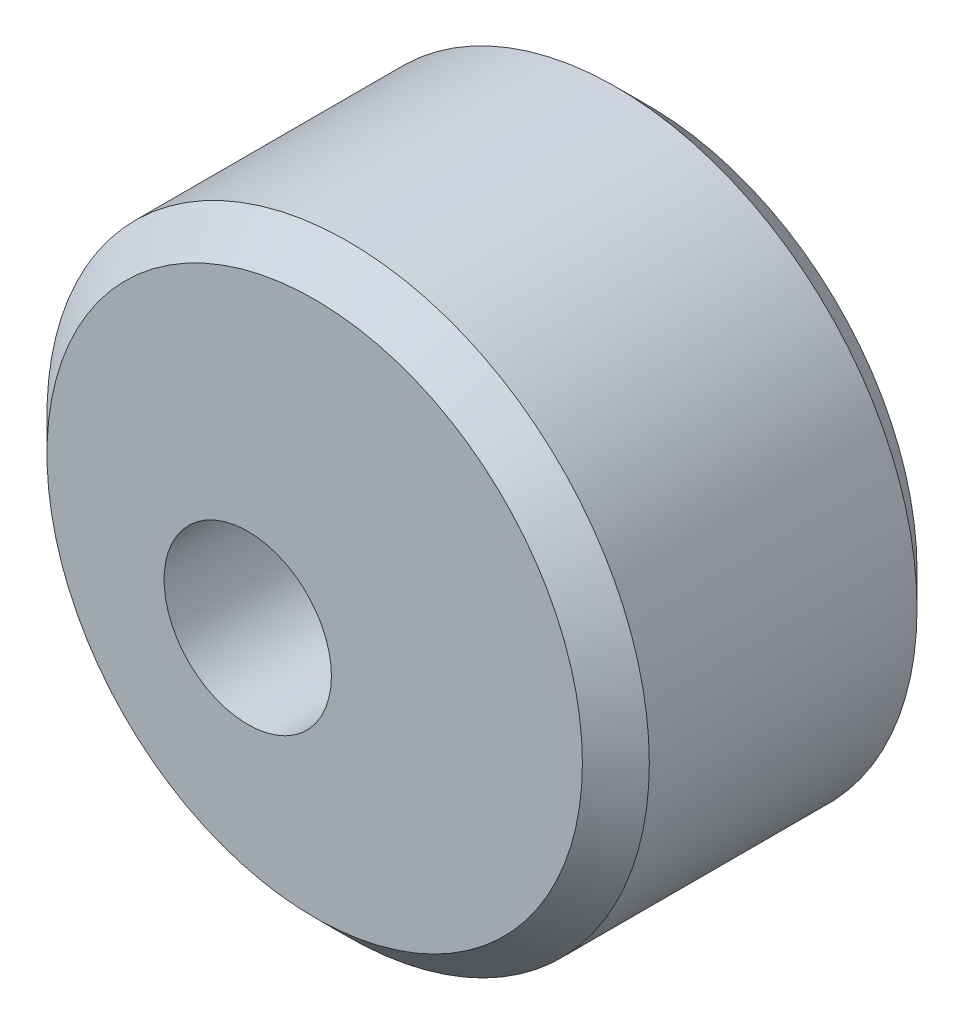
SolidWorks part; units mm, degrees
ref_plane "前视基准面" through (0, 0, 0) normal (0, 0, 1) x (1, 0, 0)
ref_plane "上视基准面" through (0, 0, 0) normal (0, 1, 0) x (1, 0, 0)
ref_plane "右视基准面" through (0, 0, 0) normal (1, 0, 0) x (0, 0, -1)
sketch "草图1" plane through (0, 0, 0) normal (0, 0, 1) x (1, 0, 0)
  circle A0 centre (0, 0) radius 9
  dimension "D1" = 18
extrude "凸台-拉伸1" add sketch "草图1" along normal mid plane 10
chamfer "倒角1" distance 1 angle 45 2 edges at (9, 0, -5) (9, 0, 5)
hole_wizard "M6 螺纹孔1" positions "草图3" profile "草图4" tap size "M6" standard "GB" end condition up to next
sketch "草图3" plane through (0, 0, 5) normal (0, 0, 1) x (1, 0, 0)
  line L0 (0, -5.5) -> (0, 5.5) construction
  line L1 (5.5, 0) -> (-5.5, 0) construction
  point P0 (-2, -1.5)
  dimension "D1" = 2
  dimension "D2" = 1.5
sketch "草图4" plane through (-2, -1.5, 5) normal (1, 0, 0) x (0, -1, 0)
  line L0 (0, 0) -> (0, 10)
  line L1 (0, 10) -> (2.5, 10)
  line L2 (2.5, 10) -> (2.5, 0)
  line L5 (2.5, 0) -> (0, 0)
  line L11 (0, -6.35) -> (0, 107.95) construction
  dimension "通孔螺纹孔钻头直径" = 5
  dimension "通孔螺纹孔钻头深度" = 10
cosmetic thread "孔螺纹线1" parameters "D2"=6
sketch "草图5" plane through (0, 0, 0) normal (1, 0, 0) x (0, 0, -1)
  line L0 (0, -9) -> (0, -6.5)
  line L1 (-4, -9) -> (4, -9) construction
  line L2 (0, 9.9) -> (0, -9.9) construction
  line L3 (0, -6.5) -> (2.5, -9)
  line L4 (2.5, -9) -> (0, -9)
  dimension "D1" = 45
  dimension "D2" = 2.5
revolve "切除-旋转1" cut sketch "草图5" angle 360 about L0
